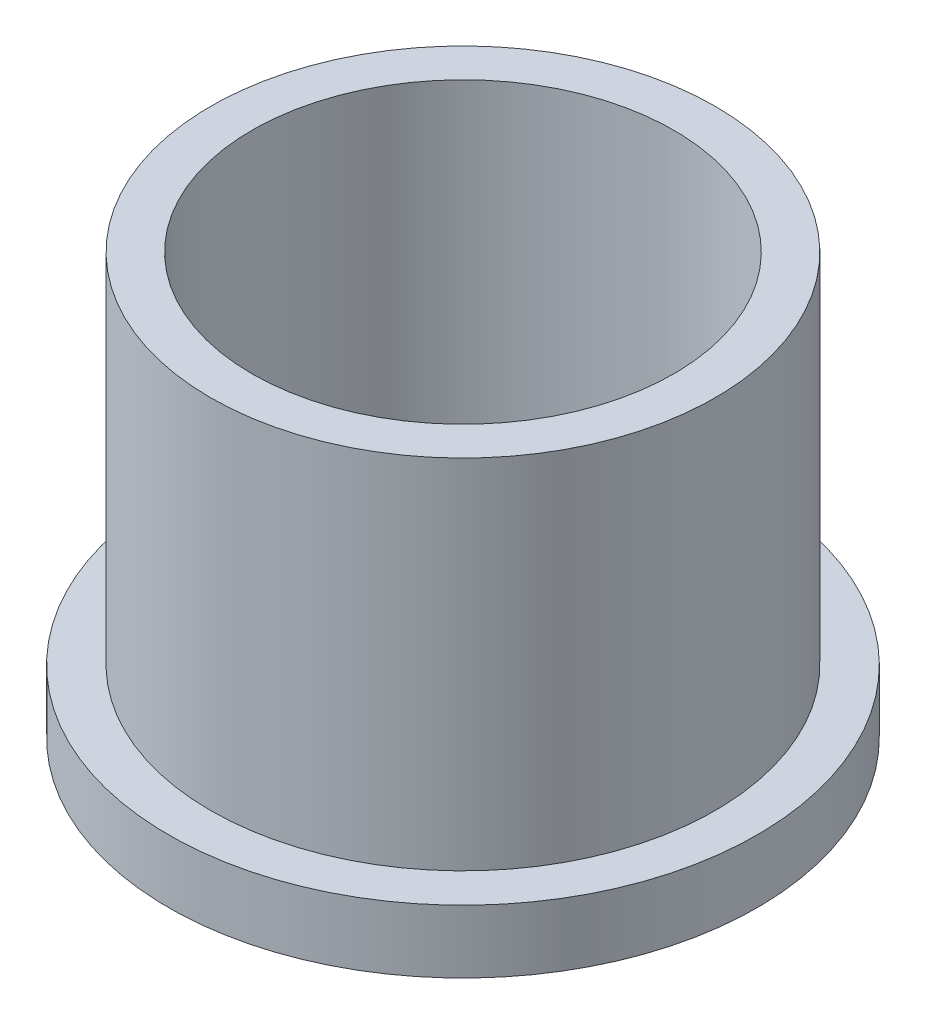
SolidWorks part; units mm, degrees
material "Brass"
ref_plane "Front" through (0, 0, 0) normal (0, 0, 1) x (1, 0, 0)
ref_plane "Top" through (0, 0, 0) normal (0, 1, 0) x (1, 0, 0)
ref_plane "Right" through (0, 0, 0) normal (1, 0, 0) x (0, 0, -1)
sketch "Sketch1" plane through (0, 0, 0) normal (0, 1, 0) x (1, 0, 0)
  circle A0 centre (0, 0) radius 15.9258
  circle A1 centre (0, 0) radius 19.05
  circle A2 centre (0, 0) radius 22.225
  dimension "ID" = 31.8516
  dimension "OD" = 38.1
  dimension "FlangeOD" = 44.45
sketch "Sketch2" plane through (0, 0, 0) normal (0, 1, 0) x (1, 0, 0)
  circle A0 centre (0, 0) radius 15.9258 construction
  circle A1 centre (0, 0) radius 19.05 construction
  circle A2 centre (0, 0) radius 15.9258
  circle A3 centre (0, 0) radius 19.05
extrude "Boss-Extrude1" add sketch "Sketch2" along normal blind 31.75
sketch "Sketch3" plane through (0, 0, 0) normal (0, 1, 0) x (1, 0, 0)
  circle A0 centre (0, 0) radius 22.225 construction
  circle A1 centre (0, 0) radius 19.05 construction
  circle A2 centre (0, 0) radius 22.225
  circle A3 centre (0, 0) radius 19.05
extrude "Boss-Extrude2" add sketch "Sketch3" along normal blind 4.7625
